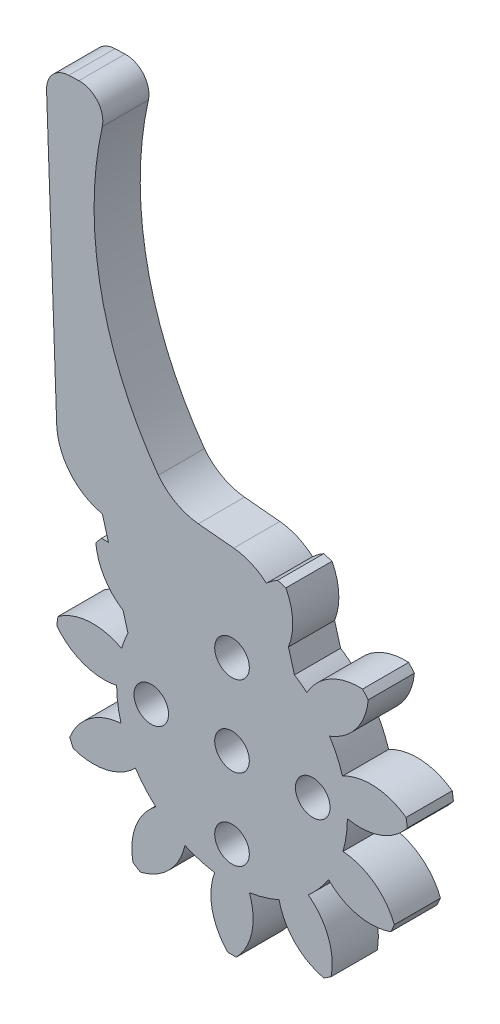
SolidWorks part; units mm, degrees
ref_plane "Спереди" through (0, 0, 0) normal (0, 0, 1) x (1, 0, 0)
ref_plane "Сверху" through (0, 0, 0) normal (0, 1, 0) x (1, 0, 0)
ref_plane "Справа" through (0, 0, 0) normal (1, 0, 0) x (0, 0, -1)
other "Configuration Table"
sketch "Эскиз1" plane through (0, 0, 0) normal (0, 0, 1) x (1, 0, 0)
  arc A1 (14.0713, -6.0135) -> (9.622, -2.739) centre (9.2497, -7.9048) ccw
  arc A2 (9.622, -2.739) -> (10.0039, -0.0828) centre (0, 0) ccw
  arc A3 (10.0039, -0.0828) -> (15.1955, 1.8056) centre (11.1021, 4.9787) ccw
  arc A4 (15.1955, 1.8056) -> (15.0886, 2.5486) centre (0, 0) ccw
  arc A5 (15.0886, 2.5486) -> (9.5753, 2.8979) centre (12.055, -1.6492) ccw
  arc A6 (9.5753, 2.8979) -> (8.4606, 5.3388) centre (0, 0) ccw
  arc A7 (8.4606, 5.3388) -> (11.8071, 9.7342) centre (6.648, 10.1906) ccw
  arc A8 (11.8071, 9.7342) -> (11.3155, 10.3016) centre (0, 0) ccw
  arc A9 (3.9497, 14.7838) -> (1.3417, 9.9138) centre (6.508, 10.2805) ccw
  arc A10 (1.3417, 9.9138) -> (-1.3417, 9.9138) centre (0, 0) ccw
  arc A11 (-1.3417, 9.9138) -> (-3.9497, 14.7838) centre (-6.508, 10.2805) ccw
  arc A12 (-3.9497, 14.7838) -> (-4.67, 14.5723) centre (0, 0) ccw
  arc A13 (-4.67, 14.5723) -> (-4.2311, 9.0654) centre (-0.0832, 12.167) ccw
  arc A14 (-4.2311, 9.0654) -> (-6.4886, 7.6147) centre (0, 0) ccw
  arc A15 (-6.4886, 7.6147) -> (-11.3155, 10.3016) centre (-11.0329, 5.13) ccw
  arc A16 (-11.3155, 10.3016) -> (-11.8071, 9.7342) centre (0, 0) ccw
  arc A17 (-11.8071, 9.7342) -> (-8.4606, 5.3388) centre (-6.648, 10.1906) ccw
  arc A18 (-8.4606, 5.3388) -> (-9.5753, 2.8979) centre (0, 0) ccw
  arc A19 (-9.5753, 2.8979) -> (-15.0886, 2.5486) centre (-12.055, -1.6492) ccw
  arc A20 (-15.0886, 2.5486) -> (-15.1955, 1.8056) centre (0, 0) ccw
  arc A21 (-15.1955, 1.8056) -> (-10.0039, -0.0828) centre (-11.1021, 4.9787) ccw
  arc A22 (-10.0039, -0.0828) -> (-9.622, -2.739) centre (0, 0) ccw
  arc A23 (-6.6137, -7.5062) -> (-8.5864, -12.6664) centre (-3.5077, -11.6507) ccw
  arc A24 (-8.5864, -12.6664) -> (-7.9548, -13.0722) centre (0, 0) ccw
  arc A25 (-7.9548, -13.0722) -> (-4.0804, -9.1342) centre (-9.1407, -8.0306) ccw
  arc A26 (-4.0804, -9.1342) -> (-1.5057, -9.8903) centre (0, 0) ccw
  arc A27 (-1.5057, -9.8903) -> (-0.3753, -15.2978) centre (3.348, -11.6976) ccw
  arc A28 (-0.3753, -15.2978) -> (0.3753, -15.2978) centre (0, 0) ccw
  arc A29 (0.3753, -15.2978) -> (1.5057, -9.8903) centre (-3.348, -11.6976) ccw
  arc A30 (1.5057, -9.8903) -> (4.0804, -9.1342) centre (0, 0) ccw
  arc A31 (4.0804, -9.1342) -> (7.9548, -13.0722) centre (9.1407, -8.0306) ccw
  arc A32 (7.9548, -13.0722) -> (8.5864, -12.6664) centre (0, 0) ccw
  arc A33 (8.5864, -12.6664) -> (6.6137, -7.5062) centre (3.5077, -11.6507) ccw
  arc A34 (6.6137, -7.5062) -> (8.371, -5.4782) centre (0, 0) ccw
  arc A35 (8.371, -5.4782) -> (13.7594, -6.6963) centre (12.0313, -1.8139) ccw
  arc A36 (13.7594, -6.6963) -> (14.0713, -6.0135) centre (0, 0) ccw
  arc A37 (-9.622, -2.739) -> (-14.0713, -6.0135) centre (-9.2497, -7.9048) ccw
  arc A38 (-14.0713, -6.0135) -> (-13.7594, -6.6963) centre (0, 0) ccw
  arc A39 (-13.7594, -6.6963) -> (-8.371, -5.4782) centre (-12.0313, -1.8139) ccw
  arc A40 (-8.371, -5.4782) -> (-6.6137, -7.5062) centre (0, 0) ccw
  arc A41 (11.3155, 10.3016) -> (6.4886, 7.6147) centre (11.0329, 5.13) ccw
  arc A42 (6.4886, 7.6147) -> (4.2311, 9.0654) centre (0, 0) ccw
  arc A43 (4.2311, 9.0654) -> (4.67, 14.5723) centre (0.0832, 12.167) ccw
  arc A44 (4.67, 14.5723) -> (3.9497, 14.7838) centre (0, 0) ccw
  circle A45 centre (0, 0) radius 1.5
  point P102 (0, 0)
  dimension "D3" = 3
extrude "Бобышка-Вытянуть1" add sketch "Эскиз1" along normal blind 4
sketch "Эскиз2" plane through (0, 0, 4) normal (0, 0, 1) x (1, 0, 0)
  line L29 (-12.3695, 43.7128) -> (0, 0) construction
  line L30 (-13.2718, 43.6807) -> (-14.1496, 43.6494)
  line L31 (-11.2391, 12.1731) -> (-7.2166, -2.0421)
  line L32 (-15.1982, 16.8864) -> (-16.0772, 41.5796)
  line L33 (0.1505, 15.3016) -> (-2.9178, 15.5937)
  line L34 (4.4878, 11.6855) -> (7.2166, 2.0421)
  arc A40 (-13.2718, 43.6807) -> (-11.2485, 41.2471) centre (-13.2006, 41.682) cw
  arc A41 (-14.1496, 43.6494) -> (-16.0772, 41.5796) centre (-14.0785, 41.6507) ccw
  circle A42 centre (0, 0) radius 1.5
  arc A43 (-6.3906, 17.5013) -> (-11.2485, 41.2471) centre (17.6968, 34.7988) cw
  arc A44 (4.4878, 11.6855) -> (0.1505, 15.3016) centre (-0.3233, 10.3241) ccw
  arc A45 (-11.2391, 12.1731) -> (-15.1982, 16.8864) centre (-10.2014, 17.0642) cw
  arc A46 (-2.9178, 15.5937) -> (-6.3906, 17.5013) centre (-2.444, 20.5712) cw
  arc A47 (7.2166, 2.0421) -> (-7.2166, -2.0421) centre (0, 0) cw
  point P68 (-7.9367, 17.8597)
  point P69 (-8.1684, 28.8665)
extrude "Бобышка-Вытянуть2" add sketch "Эскиз2" against normal blind 4
sketch "Эскиз3" plane through (0, 0, 4) normal (0, 0, 1) x (1, 0, 0)
  circle A0 centre (0, 0) radius 7 construction
  circle A1 centre (0, 7) radius 1.5
  circle A2 centre (7, 0) radius 1.5
  circle A3 centre (0, -7) radius 1.5
  circle A4 centre (-7, 0) radius 1.5
extrude "Вырез-Вытянуть1" cut sketch "Эскиз3" against normal blind 10
